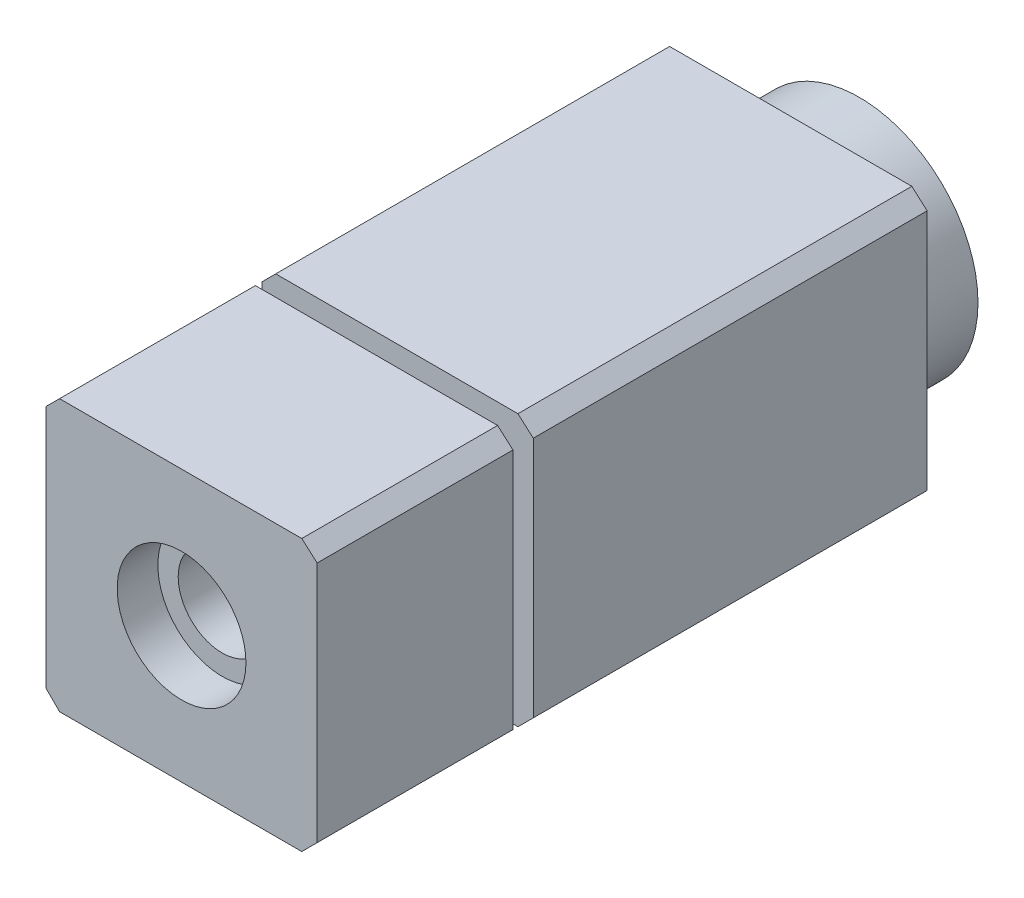
SolidWorks part; units mm, degrees
ref_plane "前视基准面" through (0, 0, 0) normal (0, 0, 1) x (1, 0, 0)
ref_plane "上视基准面" through (0, 0, 0) normal (0, 1, 0) x (1, 0, 0)
ref_plane "右视基准面" through (0, 0, 0) normal (1, 0, 0) x (0, 0, -1)
other "Configuration Table"
sketch "草图1" plane through (0, 0, 0) normal (0, 0, 1) x (1, 0, 0)
  line L0 (-20, 18) -> (-18, 20)
  line L1 (-18, 20) -> (17.7358, 20)
  line L2 (-20, 18) -> (-20, -18)
  line L3 (-18, -20) -> (17.7358, -20)
  line L4 (20, 18) -> (20, -17.7358)
  line L5 (17.7358, 20) -> (20, 18)
  line L6 (-18, -20) -> (-20, -18)
  line L7 (17.7358, -20) -> (20, -17.7358)
  dimension "D3" = 2
extrude "凸台-拉伸1" add sketch "草图1" along normal blind 80
sketch "草图3" plane through (0, 0, 80) normal (0, 0, 1) x (1, 0, 0)
  circle A0 centre (0, 0) radius 17.5
  dimension "D1" = 35
extrude "凸台-拉伸2" add sketch "草图3" along normal blind 10
sketch "草图4" plane through (0, 0, 0) normal (0, 0, -1) x (-1, 0, 0)
  circle A0 centre (0, 0) radius 17.5
  dimension "D1" = 35
extrude "凸台-拉伸3" add sketch "草图4" along normal blind 10
sketch "草图6" plane through (0, 0, -10) normal (0, 0, -1) x (-1, 0, 0)
  circle A0 centre (0, 0) radius 9.5
  dimension "D1" = 19
extrude "切除-拉伸3" cut sketch "草图6" against normal blind 6
sketch "草图7" plane through (0, 0, 90) normal (0, 0, 1) x (1, 0, 0)
  circle A0 centre (0, 0) radius 9.5
  dimension "D1" = 19
extrude "切除-拉伸4" cut sketch "草图7" against normal blind 6
sketch "草图8" plane through (0, 0, -10) normal (0, 0, -1) x (-1, 0, 0)
  circle A0 centre (0, 0) radius 6.5
  dimension "D1" = 13
extrude "切除-拉伸5" cut sketch "草图8" against normal blind 100
sketch "草图9" plane through (0, 0, 90) normal (0, 0, 1) x (1, 0, 0)
  line L0 (-20, -18) -> (-18, -20) construction
  line L1 (-18, -20) -> (17.7358, -20) construction
  line L2 (17.7358, -20) -> (20, -17.7358) construction
  line L3 (20, -17.7358) -> (20, 18) construction
  line L4 (20, 18) -> (17.7358, 20) construction
  line L5 (17.7358, 20) -> (-18, 20) construction
  line L6 (-20, 18) -> (-20, -18) construction
  line L7 (-18, 20) -> (-20, 18) construction
  line L8 (-20, -18) -> (-18, -20)
  line L9 (-18, -20) -> (17.7358, -20)
  line L10 (17.7358, -20) -> (20, -17.7358)
  line L11 (20, -17.7358) -> (20, 18)
  line L12 (20, 18) -> (17.7358, 20)
  line L13 (17.7358, 20) -> (-18, 20)
  line L14 (-20, 18) -> (-20, -18)
  line L15 (-18, 20) -> (-20, 18)
  circle A0 centre (0, 0) radius 17.5
  circle A1 centre (0, 0) radius 14.5
  dimension "D1" = 35
  dimension "D2" = 29
sketch "草图10" plane through (0, 0, 0) normal (0, 0, -1) x (-1, 0, 0)
  line L8 (20, -18) -> (20, 18)
  line L9 (20, 18) -> (18, 20)
  line L10 (18, 20) -> (-17.7358, 20)
  line L11 (-17.7358, 20) -> (-20, 18)
  line L12 (-20, 18) -> (-20, -17.7358)
  line L13 (-20, -17.7358) -> (-17.7358, -20)
  line L14 (-17.7358, -20) -> (18, -20)
  line L15 (18, -20) -> (20, -18)
  line L16 (20, -18) -> (20, 18)
  line L17 (20, 18) -> (18, 20)
  line L18 (18, 20) -> (-17.7358, 20)
  line L19 (-17.7358, 20) -> (-20, 18)
  line L20 (-20, 18) -> (-20, -17.7358)
  line L21 (-20, -17.7358) -> (-17.7358, -20)
  line L22 (-17.7358, -20) -> (18, -20)
  line L23 (18, -20) -> (20, -18)
  circle A0 centre (0, 0) radius 17.5 construction
  circle A1 centre (0, 0) radius 17.5
  dimension "D1" = 0
ref_plane "基准面1" through (0, 0, 61.11) normal (0, 0, 1) x (1, 0, 0)
sketch "草图11" plane through (0, 0, 61.11) normal (0, 0, 1) x (1, 0, 0)
  line L0 (17.7358, -20) -> (-18, -20) construction
  line L1 (20, -17.7358) -> (17.7358, -20) construction
  line L2 (20, 18) -> (20, -17.7358) construction
  line L3 (17.7358, 20) -> (20, 18) construction
  line L4 (-18, 20) -> (17.7358, 20) construction
  line L5 (-20, 18) -> (-18, 20) construction
  line L6 (-20, -18) -> (-20, 18) construction
  line L7 (17.7358, -20) -> (-18, -20)
  line L8 (20, -17.7358) -> (17.7358, -20)
  line L9 (20, 18) -> (20, -17.7358)
  line L10 (17.7358, 20) -> (20, 18)
  line L11 (-18, 20) -> (17.7358, 20)
  line L12 (-20, 18) -> (-18, 20)
  line L13 (-20, -18) -> (-20, 18)
  line L14 (-18, -20) -> (-20, -18) construction
  line L15 (-18, -20) -> (-20, -18)
  circle A0 centre (0, 0) radius 17.5 construction
  circle A1 centre (0, 0) radius 14.5 construction
  circle A2 centre (0, 0) radius 17.5
  circle A3 centre (0, 0) radius 14.5
  point P9 (-14.5, 0)
extrude "切除-拉伸8" cut sketch "草图11" against normal blind 3 contours L13 L12 L11 L10 L9 L8 L7 L15 | A3
sketch "草图12" plane through (0, 0, 61.11) normal (0, 0, 1) x (1, 0, 0)
  line L0 (-20, -18) -> (-18, -20) construction
  line L1 (-18, -20) -> (17.7358, -20) construction
  line L2 (17.7358, -20) -> (20, -17.7358) construction
  line L3 (20, -17.7358) -> (20, 18) construction
  line L4 (20, 18) -> (17.7358, 20) construction
  line L5 (17.7358, 20) -> (-18, 20) construction
  line L6 (-20, 18) -> (-20, -18) construction
  line L7 (-18, 20) -> (-20, 18) construction
  line L8 (-20, -18) -> (-18, -20)
  line L9 (-18, -20) -> (17.7358, -20)
  line L10 (17.7358, -20) -> (20, -17.7358)
  line L11 (20, -17.7358) -> (20, 18)
  line L12 (20, 18) -> (17.7358, 20)
  line L13 (17.7358, 20) -> (-18, 20)
  line L14 (-20, 18) -> (-20, -18)
  line L15 (-18, 20) -> (-20, 18)
sketch "草图13" plane through (0, 0, 80) normal (0, 0, 1) x (1, 0, 0)
  line L8 (-20, 18) -> (-20, -18)
  line L9 (-20, -18) -> (-18, -20)
  line L10 (-18, -20) -> (17.7358, -20)
  line L11 (17.7358, -20) -> (20, -17.7358)
  line L12 (20, -17.7358) -> (20, 18)
  line L13 (20, 18) -> (17.7358, 20)
  line L14 (17.7358, 20) -> (-18, 20)
  line L15 (-18, 20) -> (-20, 18)
  line L16 (-20, 18) -> (-20, -18)
  line L17 (-20, -18) -> (-18, -20)
  line L18 (-18, -20) -> (17.7358, -20)
  line L19 (17.7358, -20) -> (20, -17.7358)
  line L20 (20, -17.7358) -> (20, 18)
  line L21 (20, 18) -> (17.7358, 20)
  line L22 (17.7358, 20) -> (-18, 20)
  line L23 (-18, 20) -> (-20, 18)
  circle A0 centre (0, 0) radius 17.5 construction
  circle A1 centre (0, 0) radius 17.5
  dimension "D1" = 0
extrude "凸台-拉伸5" add sketch "草图13" along normal blind 10
